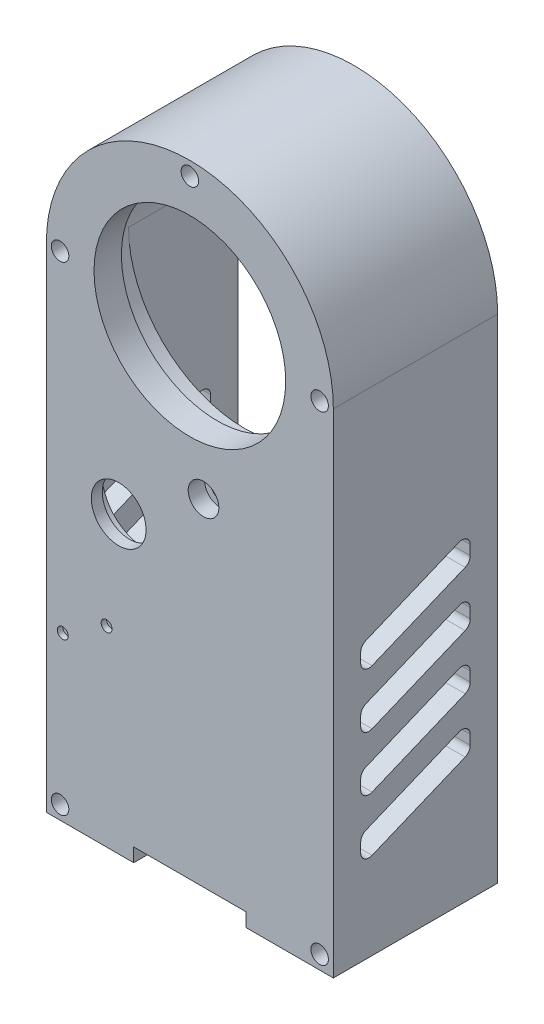
SolidWorks part; units mm, degrees
ref_plane "Front Plane" through (0, 0, 0) normal (0, 0, 1) x (1, 0, 0)
ref_plane "Top Plane" through (0, 0, 0) normal (0, 1, 0) x (1, 0, 0)
ref_plane "Right Plane" through (0, 0, 0) normal (1, 0, 0) x (0, 0, -1)
sketch "Sketch1" plane through (0, 0, 0) normal (0, 0, 1) x (1, 0, 0)
  circle A1 centre (0, 0) radius 17.5
  circle A2 centre (0, 0) radius 21.2
extrude "Boss-Extrude1" add sketch "Sketch1" along normal blind 5
sketch "Sketch2" plane through (0, 0, 5) normal (0, 0, 1) x (1, 0, 0)
  line L4 (26.2, 0) -> (26.2, -90)
  line L5 (26.2, -90) -> (-26.2, -90)
  line L6 (-26.2, 0) -> (-26.2, -90)
  circle A0 centre (0, 0) radius 21.2
  arc A3 (26.2, 0) -> (-26.2, 0) centre (0, 0) ccw
extrude "Boss-Extrude2" add sketch "Sketch2" against normal blind 5
sketch "Sketch4" plane through (0, 0, 0) normal (0, 0, -1) x (-1, 0, 0)
  line L0 (-21.2, 0) -> (-21.2, -85)
  line L1 (-21.2, -85) -> (21.2, -85)
  line L2 (21.2, -85) -> (21.2, 0)
  line L3 (-26.2, 0) -> (-26.2, -90)
  line L4 (-26.2, -90) -> (26.2, -90)
  line L5 (26.2, -90) -> (26.2, 0)
  line L6 (-26.2, 0) -> (-26.2, -90)
  line L7 (-26.2, -90) -> (26.2, -90)
  line L8 (26.2, -90) -> (26.2, 0)
  arc A0 (21.2, 0) -> (-21.2, 0) centre (0, 0) ccw
  arc A1 (26.2, 0) -> (-26.2, 0) centre (0, 0) ccw
  arc A2 (26.2, 0) -> (-26.2, 0) centre (0, 0) ccw
  dimension "D1" = 0
  dimension "D2" = 5
extrude "Boss-Extrude3" add sketch "Sketch4" along normal blind 25
sketch "Sketch5" plane through (0, 0, 0) normal (0, 0, -1) x (-1, 0, 0)
  circle A0 centre (12.9951, -36.2428) radius 5
extrude "Cut-Extrude1" cut sketch "Sketch5" against normal through all
sketch "Sketch7" plane through (0, 0, 0) normal (0, 0, -1) x (-1, 0, 0)
  circle A0 centre (12.9951, -36.2428) radius 8.1
extrude "Cut-Extrude2" cut sketch "Sketch7" against normal blind 3
sketch "Sketch10" plane through (0, -90, 0) normal (0, -1, 0) x (1, 0, 0)
  circle A1 centre (15.5, -5.5) radius 1.65
  circle A2 centre (15.5, -5.5) radius 1.65
  circle A3 centre (15.5, -36.5) radius 1.65
  circle A4 centre (15.5, -36.5) radius 1.65
  circle A5 centre (-15.5, -36.5) radius 1.65
  circle A6 centre (-15.5, -36.5) radius 1.65
  circle A7 centre (-15.5, -5.5) radius 1.65
  circle A8 centre (-15.5, -5.5) radius 1.65
  dimension "D1" = 0
  dimension "D2" = 0
  dimension "D3" = 0
  dimension "D4" = 0
extrude "Cut-Extrude3" cut sketch "Sketch10" against normal blind 23
sketch "Sketch11" plane through (0, 0, -25) normal (0, 0, -1) x (-1, 0, 0)
  circle A0 centre (-23.7, -87.5) radius 1.6
  circle A1 centre (23.7, -87.5) radius 1.6
  circle A2 centre (0, 23.7) radius 1.6
  circle A3 centre (23.7, 0) radius 1.6
  circle A5 centre (-23.7, 0) radius 1.6
  circle A6 centre (0, -23.7) radius 1.6 [skipped]
  point P11 (0, 0)
  dimension "D1" = 4
extrude "Cut-Extrude4" cut sketch "Sketch11" against normal blind 33
sketch "Sketch12" plane through (0, 0, -25) normal (0, 0, -1) x (-1, 0, 0)
  line L0 (-26.2, -90) -> (26.2, -90) construction
  line L1 (-10.25, -92.5) -> (10.25, -92.5)
  line L2 (-10.25, -92.5) -> (-10.25, -87.5)
  line L3 (-10.25, -87.5) -> (10.25, -87.5)
  line L4 (10.25, -92.5) -> (10.25, -87.5)
  line L5 (-10.25, -92.5) -> (10.25, -87.5) construction
  line L6 (-10.25, -87.5) -> (10.25, -92.5) construction
  point P0 (0, -90)
extrude "Cut-Extrude5" cut sketch "Sketch12" against normal through all
sketch "Sketch13" plane through (0, 0, 0) normal (0, 0, -1) x (-1, 0, 0)
  line L0 (9.3688, -39.4633) -> (-14.3559, -12.7495) construction
  circle A0 centre (-2.4936, -26.1064) radius 1.6
extrude "Cut-Extrude6" cut sketch "Sketch13" against normal through all
sketch "Sketch14" plane through (0, 0, 5) normal (0, 0, 1) x (1, 0, 0)
  line L0 (-9.3688, -39.4633) -> (14.3559, -12.7495) construction
  circle A0 centre (2.4936, -26.1064) radius 2.8
extrude "Cut-Extrude7" cut sketch "Sketch14" against normal blind 3
sketch "Sketch15" plane through (0, 0, 0) normal (0, 0, -1) x (-1, 0, 0)
  line L0 (21.2, -85) -> (21.2, 0) construction
  line L1 (21.2, -11.6705) -> (21.2, 0)
  line L2 (-21.2, 0) -> (-21.2, -85) construction
  line L3 (-21.2, 0) -> (-21.2, -11.6705)
  arc A0 (-21.2, 0) -> (21.2, 0) centre (0, 0) ccw
  arc A1 (-21.2, -11.6705) -> (21.2, -11.6705) centre (0, 0) ccw
  circle A2 centre (0, 0) radius 24.2 construction
  circle A3 centre (0, 0) radius 21.2 construction
  dimension "D1" = 3
extrude "Boss-Extrude4" add sketch "Sketch15" along normal blind 5
sketch "Sketch17" plane through (0, 0, 5) normal (0, 0, 1) x (1, 0, 0)
  line L0 (0, 0) -> (26.2, 0)
  line L1 (0, 0) -> (0, 26.2)
  arc A0 (26.2, 0) -> (-26.2, 0) centre (0, 0) ccw construction
sketch "Sketch19" plane through (26.2, 0, 0) normal (1, 0, 0) x (0, 0, -1)
  line L0 (0, -61.0023) -> (0, -62.7551)
  line L1 (20, -53.9606) -> (20, -55.7135)
  line L2 (0, -11.6705) -> (0, -85) construction
  line L3 (0, -71.0023) -> (0, -72.7551)
  line L4 (2.074, -64.1409) -> (19.074, -57.0993)
  line L5 (20, -63.9606) -> (20, -65.7135)
  line L6 (0.926, -59.6164) -> (17.926, -52.5748)
  line L7 (0, -51.0023) -> (0, -52.7551)
  line L8 (2.074, -74.1409) -> (19.074, -67.0993)
  line L11 (0.926, -69.6164) -> (17.926, -62.5748)
  line L12 (0, -11.6705) -> (0, -85) construction
  line L13 (20, -11.6705) -> (20, -85) construction
  line L14 (20, -43.9606) -> (20, -45.7135)
  line L15 (2.074, -54.1409) -> (19.074, -47.0993)
  line L16 (0.926, -49.6164) -> (17.926, -42.5748)
  line L17 (0, -41.0023) -> (0, -42.7551)
  line L18 (20, -33.9606) -> (20, -35.7135)
  line L19 (2.074, -44.1409) -> (19.074, -37.0993)
  line L20 (0.926, -39.6164) -> (17.926, -32.5748)
  arc A0 (20, -63.9606) -> (17.926, -62.5748) centre (18.5, -63.9606) ccw
  arc A1 (19.074, -67.0993) -> (20, -65.7135) centre (18.5, -65.7135) ccw
  arc A2 (2.074, -74.1409) -> (0, -72.7551) centre (1.5, -72.7551) cw
  arc A3 (0, -71.0023) -> (0.926, -69.6164) centre (1.5, -71.0023) cw
  arc A4 (20, -53.9606) -> (17.926, -52.5748) centre (18.5, -53.9606) ccw
  arc A5 (19.074, -57.0993) -> (20, -55.7135) centre (18.5, -55.7135) ccw
  arc A6 (2.074, -64.1409) -> (0, -62.7551) centre (1.5, -62.7551) cw
  arc A7 (0, -61.0023) -> (0.926, -59.6164) centre (1.5, -61.0023) cw
  arc A8 (20, -43.9606) -> (17.926, -42.5748) centre (18.5, -43.9606) ccw
  arc A9 (19.074, -47.0993) -> (20, -45.7135) centre (18.5, -45.7135) ccw
  arc A10 (2.074, -54.1409) -> (0, -52.7551) centre (1.5, -52.7551) cw
  arc A11 (0, -51.0023) -> (0.926, -49.6164) centre (1.5, -51.0023) cw
  arc A12 (20, -33.9606) -> (17.926, -32.5748) centre (18.5, -33.9606) ccw
  arc A13 (19.074, -37.0993) -> (20, -35.7135) centre (18.5, -35.7135) ccw
  arc A14 (2.074, -44.1409) -> (0, -42.7551) centre (1.5, -42.7551) cw
  arc A15 (0, -41.0023) -> (0.926, -39.6164) centre (1.5, -41.0023) cw
  dimension "D1" = 1.5
  dimension "D3" = 4
  dimension "D2" = 20
extrude "Cut-Extrude9" cut sketch "Sketch19" against normal through all
sketch "Sketch20" plane through (0, 0, 5) normal (0, 0, 1) x (1, 0, 0)
  circle A0 centre (-15.8281, -49.8568) radius 1
sketch "Sketch23" plane through (0, 0, 5) normal (0, 0, 1) x (1, 0, 0)
  circle A0 centre (-15.2, -55.0291) radius 1
  circle A1 centre (-23.2027, -60.1485) radius 1
extrude "Cut-Extrude11" cut sketch "Sketch23" against normal blind 1
